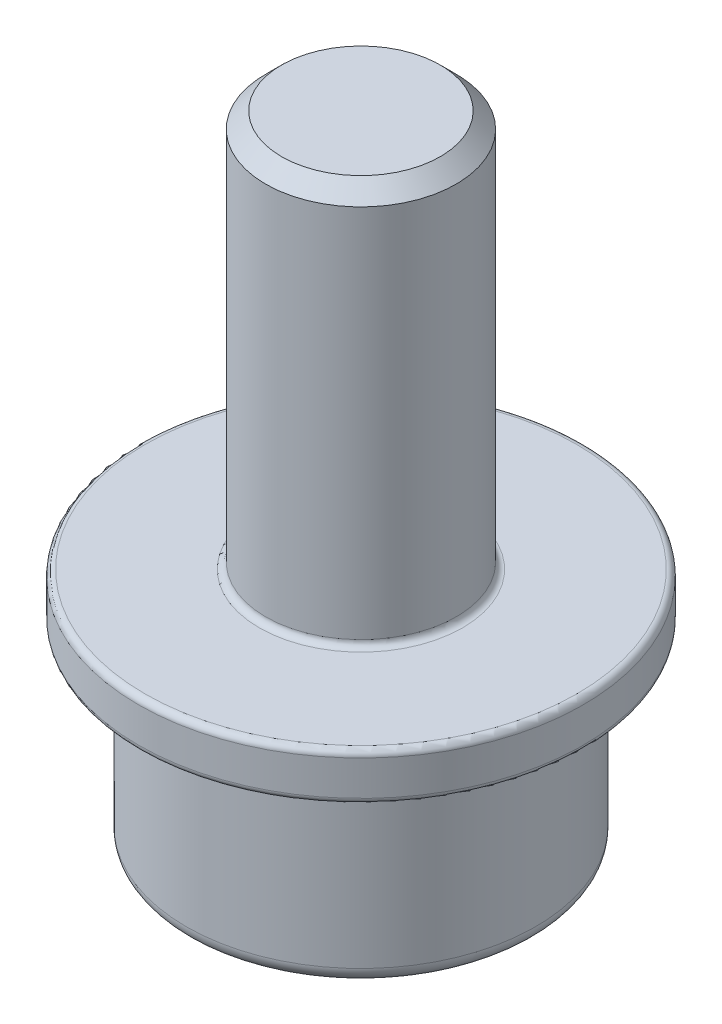
SolidWorks part; units mm, degrees
ref_plane "Front Plane" through (0, 0, 0) normal (0, 0, 1) x (1, 0, 0)
ref_plane "Top Plane" through (0, 0, 0) normal (0, 1, 0) x (1, 0, 0)
ref_plane "Right Plane" through (0, 0, 0) normal (1, 0, 0) x (0, 0, -1)
sketch "Sketch1" plane through (0, 0, 0) normal (0, 1, 0) x (1, 0, 0)
  circle A0 centre (0, 0) radius 2.75
  dimension "D1" = 5.5
extrude "Boss-Extrude1" add sketch "Sketch1" along normal blind 3
sketch "Sketch2" plane through (0, 3, 0) normal (0, 1, 0) x (1, 0, 0)
  circle A0 centre (0, 0) radius 1.5
  dimension "D1" = 3
extrude "Boss-Extrude2" add sketch "Sketch2" along normal blind 7 contours A0
sketch "Sketch3" plane through (0, 0, 0) normal (0, -1, 0) x (1, 0, 0)
  line L1 (0.9342, 0.9746) -> (-0.3769, 1.2963)
  line L2 (-0.3769, 1.2963) -> (-1.3111, 0.3217)
  line L3 (-1.3111, 0.3217) -> (-0.9342, -0.9746)
  line L4 (-0.9342, -0.9746) -> (0.3769, -1.2963)
  line L5 (0.3769, -1.2963) -> (1.3111, -0.3217)
  line L6 (1.3111, -0.3217) -> (0.9342, 0.9746)
  circle A0 centre (0, 0) radius 1.1691 construction
  dimension "D1" = 2.7
extrude "Cut-Extrude1" cut sketch "Sketch3" against normal blind 1.5
chamfer "Chamfer1" distance 0.25 distance2 0.25 6 edges at (-0.2786, 0, -1.1355) (-1.1226, 0, -0.3264) (-0.844, 0, 0.809) (0.2786, 0, 1.1355) (1.1226, 0, 0.3264) (0.844, 0, -0.809)
fillet "Fillet1" radius 0.25 1 edges at (0, 0, 2.75)
chamfer "Chamfer2" distance 0.25 angle 45 1 edges at (0, 10, 1.5)
fillet "Fillet2" radius 0.1 1 edges at (0, 3, 2.75)
sketch "Sketch4" plane through (0, 3, 0) normal (0, 1, 0) x (1, 0, 0)
  circle A0 centre (0, 0) radius 1.5
  circle A1 centre (0, 0) radius 3.5
  circle A2 centre (0, 0) radius 1.5 construction
  dimension "D1" = 7
extrude "Boss-Extrude3" add sketch "Sketch4" along normal blind 0.75
fillet "Fillet3" radius 0.1 3 edges at (0, 3.75, 1.5) (0, 3.75, 3.5) (0, 3, 3.5)
